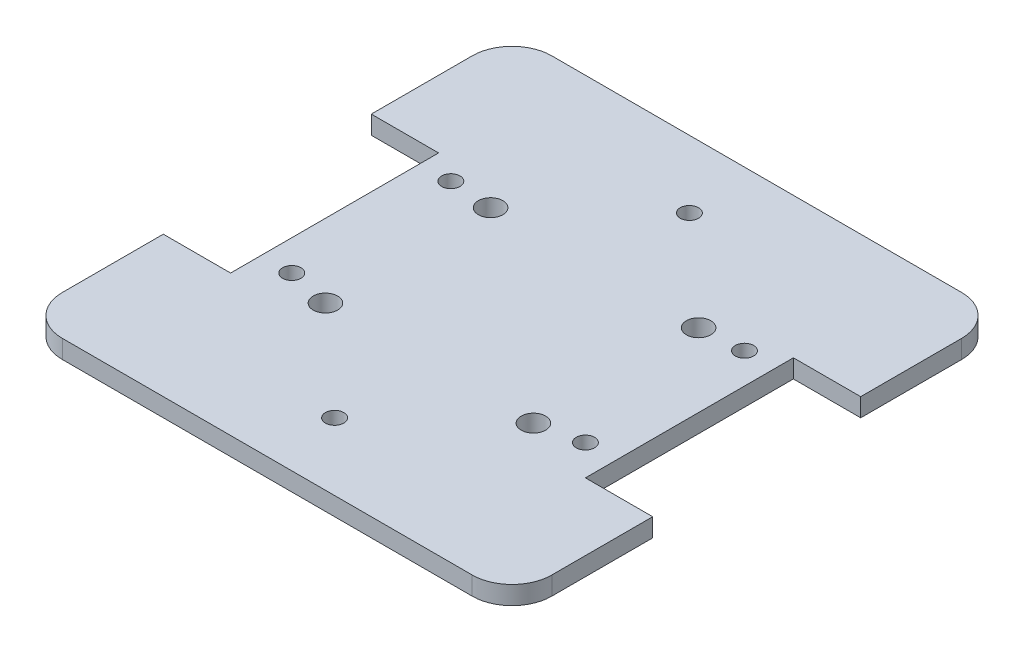
SolidWorks part; units mm, degrees
material "Acrylic (Medium-high impact)"
ref_plane "Front Plane" through (0, 0, 0) normal (0, 0, 1) x (1, 0, 0)
ref_plane "Top Plane" through (0, 0, 0) normal (0, 1, 0) x (1, 0, 0)
ref_plane "Right Plane" through (0, 0, 0) normal (1, 0, 0) x (0, 0, -1)
sketch "Sketch1" plane through (0, 0, 0) normal (0, 1, 0) x (1, 0, 0)
  line L24 (11, 40) -> (23, 40) construction
  line L25 (6.5, 0) -> (73.5, 0)
  line L26 (80, 6.5) -> (80, 23)
  line L27 (73.5, 80) -> (6.5, 80)
  line L28 (0, 73.5) -> (0, 57)
  line L29 (11, 23) -> (0, 23)
  line L30 (11, 23) -> (11, 57)
  line L31 (11, 57) -> (0, 57)
  line L32 (0, 23) -> (0, 6.5)
  line L33 (40, 80) -> (40, 0) construction
  line L34 (69, 23) -> (69, 57)
  line L35 (69, 23) -> (80, 23)
  line L36 (69, 57) -> (80, 57)
  line L37 (80, 57) -> (80, 73.5)
  line L38 (16, 54) -> (16, 28) construction
  line L39 (23, 40) -> (23, 53.5) construction
  line L40 (23, 40) -> (23, 26.5) construction
  arc A23 (6.5, 0) -> (0, 6.5) centre (6.5, 6.5) cw
  arc A24 (80, 6.5) -> (73.5, 0) centre (73.5, 6.5) cw
  arc A25 (73.5, 80) -> (80, 73.5) centre (73.5, 73.5) cw
  arc A26 (6.5, 80) -> (0, 73.5) centre (6.5, 73.5) ccw
  circle A27 centre (16, 54) radius 1.5
  circle A28 centre (16, 28) radius 1.5
  circle A29 centre (64, 28) radius 1.5
  circle A30 centre (64, 54) radius 1.5
  circle A31 centre (23, 53.5) radius 2
  circle A32 centre (23, 26.5) radius 2
  circle A33 centre (57, 26.5) radius 2
  circle A34 centre (57, 53.5) radius 2
  circle A35 centre (40, 69) radius 1.5
  circle A36 centre (40, 11) radius 1.5
  point P0 (11, 40)
  point P11 (40, 69)
  point P28 (0, 0)
  point P38 (11, 23)
  point P49 (80, 0)
  point P52 (80, 80)
  point P57 (40, 0)
  point P60 (40, 80)
  point P67 (16, 54)
  dimension "D4" = 12
  dimension "D5" = 6.5
  dimension "D6" = 13.5
  dimension "D7" = 13.5
  dimension "D16" = 11
  dimension "D17" = 3
  dimension "D18" = 3
  dimension "D12" = 4
  dimension "D14" = 4
  dimension "D19" = 3
  dimension "D2" = 80
  dimension "D3" = 80
  dimension "D8" = 11
  dimension "D9" = 23
  dimension "D10" = 34
  dimension "D11" = 5
  dimension "D13" = 26
  dimension "D15" = 26
extrude "Boss-Extrude1" add sketch "Sketch1" along normal blind 3
